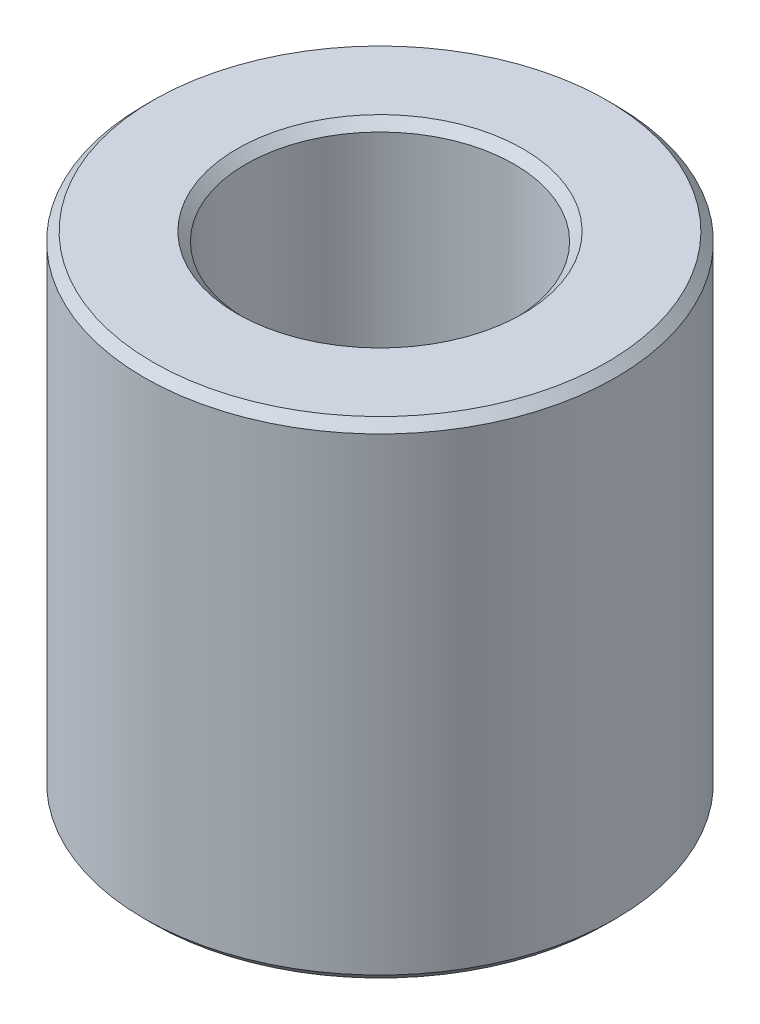
SolidWorks part; units mm, degrees
ref_plane "Plan de face" through (0, 0, 0) normal (0, 0, 1) x (1, 0, 0)
ref_plane "Plan de dessus" through (0, 0, 0) normal (0, 1, 0) x (1, 0, 0)
ref_plane "Plan de droite" through (0, 0, 0) normal (1, 0, 0) x (0, 0, -1)
sketch "Esquisse1" plane through (0, 0, 0) normal (0, 1, 0) x (1, 0, 0)
  circle A0 centre (0, 0) radius 4.55
  circle A1 centre (0, 0) radius 8
  dimension "D1" = 16
  dimension "D2" = 9.1
extrude "Boss.-Extru.1" add sketch "Esquisse1" along normal blind 16.5
chamfer "Chanfrein1" distance 0.3 angle 45 4 edges at (0, 0, 4.55) (0, 0, 8) (0, 16.5, 8) (0, 16.5, 4.55)
